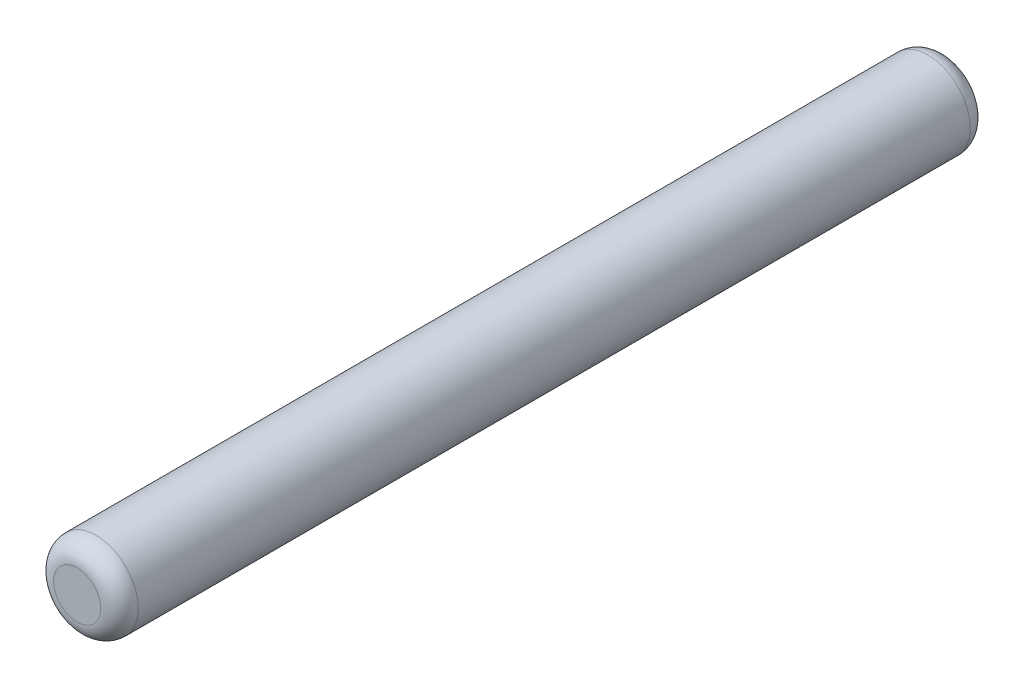
SolidWorks part; units mm, degrees
ref_plane "정면" through (0, 0, 0) normal (0, 0, 1) x (1, 0, 0)
ref_plane "윗면" through (0, 0, 0) normal (0, 1, 0) x (1, 0, 0)
ref_plane "우측면" through (0, 0, 0) normal (1, 0, 0) x (0, 0, -1)
sketch "스케치1" plane through (0, 0, 0) normal (0, 0, 1) x (1, 0, 0)
  circle A0 centre (0, 0) radius 1.8
  dimension "D1" = 3.6
extrude "보스-돌출1" add sketch "스케치1" along normal blind 37
fillet "필렛1" radius 0.8 2 edges at (1.8, 0, 0) (1.8, 0, 37)
